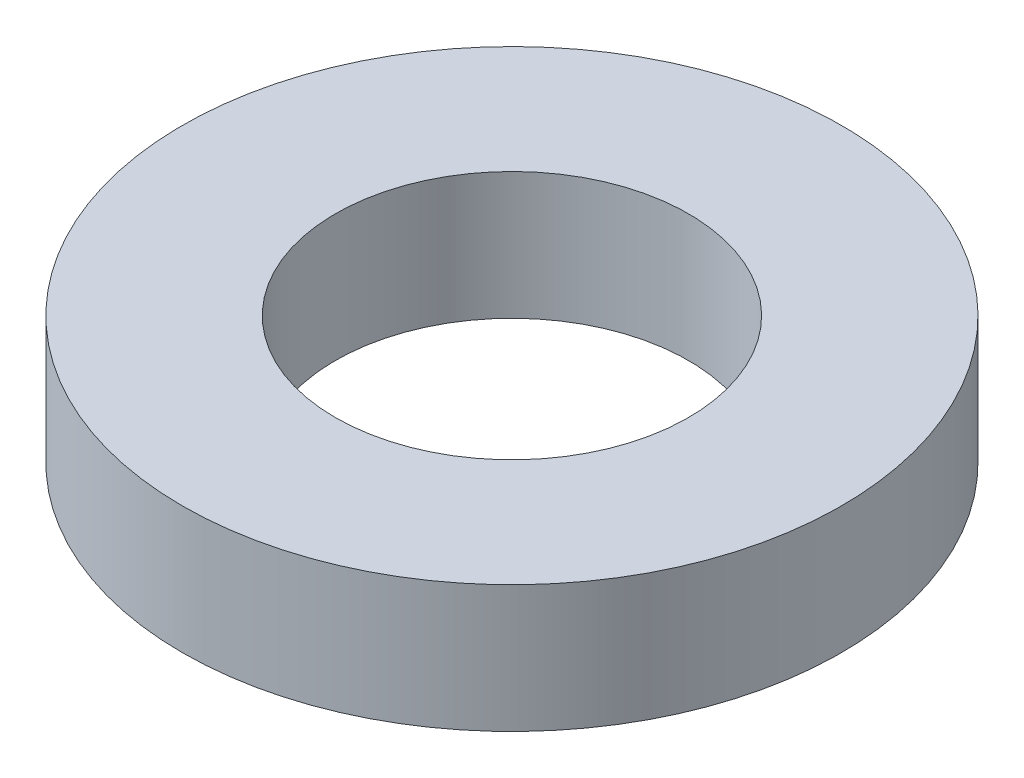
SolidWorks part; units mm, degrees
ref_plane "Front Plane" through (0, 0, 0) normal (0, 0, 1) x (1, 0, 0)
ref_plane "Top Plane" through (0, 0, 0) normal (0, 1, 0) x (1, 0, 0)
ref_plane "Right Plane" through (0, 0, 0) normal (1, 0, 0) x (0, 0, -1)
sketch "Sketch1" plane through (0, 0, 0) normal (0, 1, 0) x (1, 0, 0)
  circle A0 centre (0, 0) radius 8.89
  dimension "D1" = 17.78
extrude "Boss-Extrude1" add sketch "Sketch1" along normal blind 3.429
sketch "Sketch2" plane through (0, 3.429, 0) normal (0, 1, 0) x (1, 0, 0)
  circle A0 centre (0, 0) radius 4.7625
  dimension "D1" = 9.525
extrude "Cut-Extrude1" cut sketch "Sketch2" against normal up to surface (3.429 mm away) up to face at (0, 0, 8.89)
